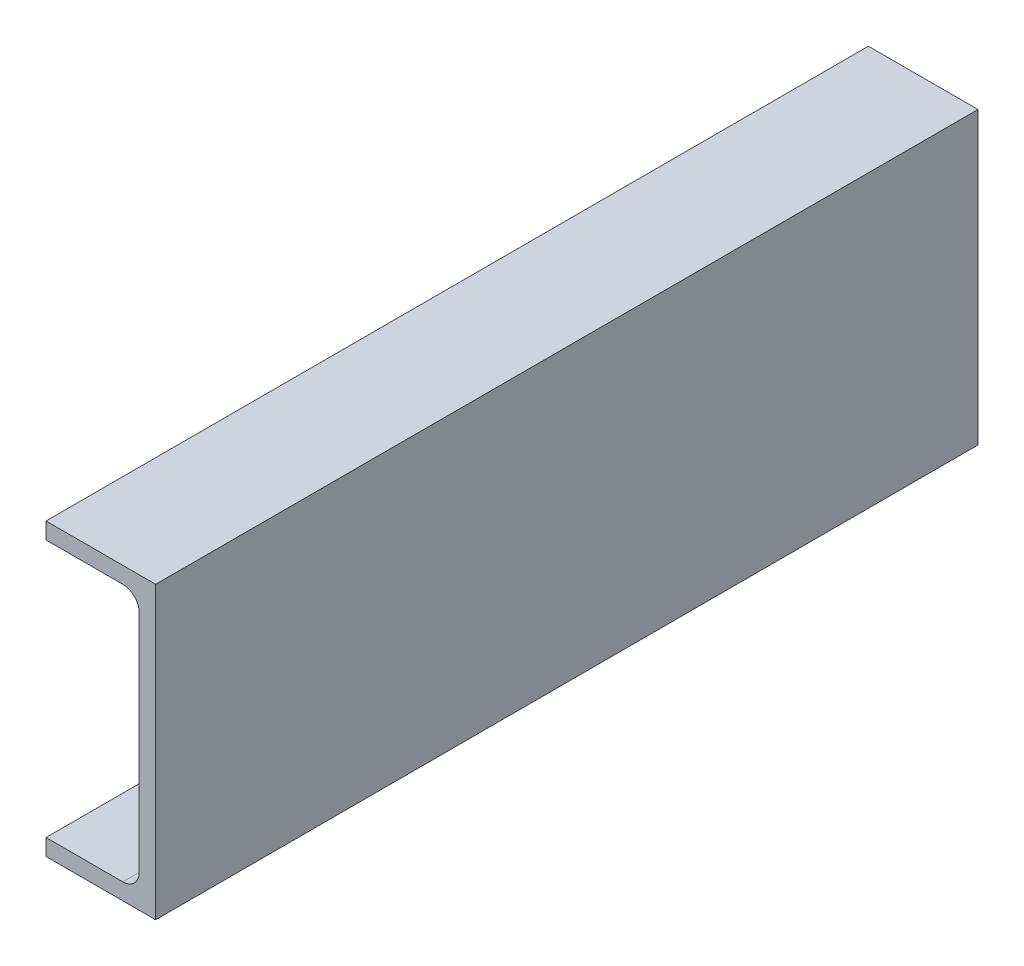
SolidWorks part; units mm, degrees
material "AISI 1020"
ref_plane "Спереди" through (0, 0, 0) normal (0, 0, 1) x (1, 0, 0)
ref_plane "Сверху" through (0, 0, 0) normal (0, 1, 0) x (1, 0, 0)
ref_plane "Справа" through (0, 0, 0) normal (1, 0, 0) x (0, 0, -1)
sketch "Эскиз1" plane through (0, 0, 0) normal (0, 0, 1) x (1, 0, 0)
  line L0 (0, 0) -> (20, 0)
  line L1 (20, 0) -> (20, 53)
  line L2 (20, 53) -> (0, 53)
  dimension "D1" = 53
  dimension "D2" = 20
extrude "Вытянуть-Тонкостенный1" add sketch "Эскиз1" along normal mid plane 150 thin thin type one direction reverse wall 3
fillet "Скругление1" radius 3 2 edges at (17, 50, 0) (17, 3, 0)
equation "\"Толщина Стеклопакета\"= 51"
equation "\"Толщина Подушек\"= 2"
equation "\"D1@Эскиз1\"=\"Толщина Стеклопакета\" + \"Толщина Подушек\""
equation "\"D1@Скругление1\"=\"D5@Вытянуть-Тонкостенный1\""
